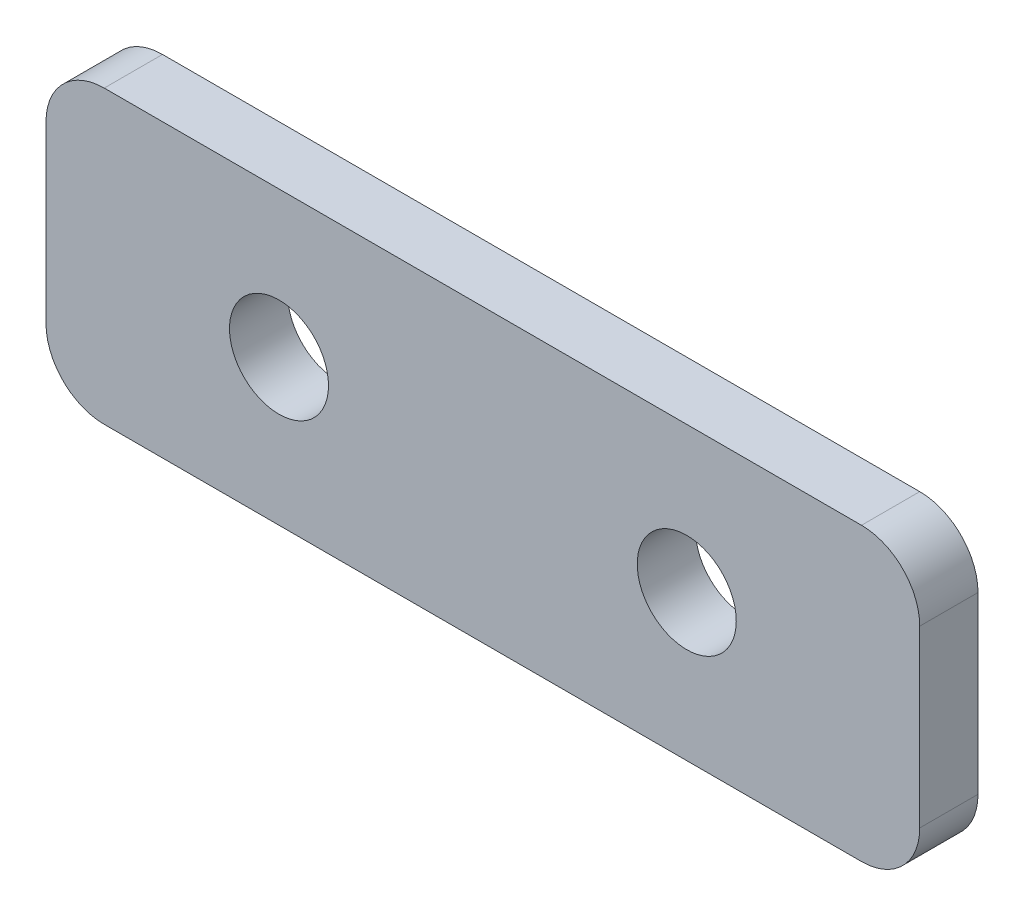
SolidWorks part; units mm, degrees
material "AISI 1020"
ref_plane "Front Plane" through (0, 0, 0) normal (0, 0, 1) x (1, 0, 0)
ref_plane "Top Plane" through (0, 0, 0) normal (0, 1, 0) x (1, 0, 0)
ref_plane "Right Plane" through (0, 0, 0) normal (1, 0, 0) x (0, 0, -1)
sketch "Sketch1" plane through (0, 0, 0) normal (0, 0, 1) x (1, 0, 0)
  line L1 (-15, -5) -> (15, -5)
  line L2 (-15, -5) -> (-15, 5)
  line L3 (-15, 5) -> (15, 5)
  line L4 (15, -5) -> (15, 5)
  line L5 (-15, -5) -> (15, 5) construction
  line L6 (-15, 5) -> (15, -5) construction
  point P0 (0, 0)
  dimension "D1" = 10
  dimension "D2" = 30
extrude "Boss-Extrude1" add sketch "Sketch1" along normal blind 2
hole_wizard "M3 Clearance Hole1" positions "Sketch2" profile "Sketch3" hole size "M3" standard "ANSI Metric" end condition through all
sketch "Sketch2" plane through (0, 0, 2) normal (0, 0, 1) x (1, 0, 0)
  line L0 (15, 5) -> (-15, 5) construction
  point P0 (-7, 0)
  point P2 (7, 0)
  dimension "D1" = 7
  dimension "D2" = 7
  dimension "D3" = 5
  dimension "D4" = 5
sketch "Sketch3" plane through (-7, 0, 2) normal (1, 0, 0) x (0, -1, 0)
  line L0 (0, 0) -> (0, 2)
  line L1 (0, 2) -> (1.7, 2)
  line L2 (1.7, 2) -> (1.7, 0)
  line L5 (1.7, 0) -> (0, 0)
  line L11 (0, -6.35) -> (0, 107.95) construction
  dimension "Thru Hole Dia." = 3.4
  dimension "Thru Hole Depth" = 2
sketch "Sketch4" plane through (0, -5, 0) normal (0, -1, 0) x (1, 0, 0)
  line L0 (-15, 2) -> (15, 2) construction
  line L1 (16.6361, 0) -> (-17.8659, 0)
  line L2 (16.6361, 0) -> (16.6361, 2)
  line L3 (16.6361, 2) -> (-17.8659, 2)
  line L4 (-17.8659, 0) -> (-17.8659, 2)
  line L5 (-15, 0) -> (15, 0) construction
fillet "Fillet1" radius 2 4 edges at (-15, 5, 1) (-15, -5, 1) (15, -5, 1) (15, 5, 1)
